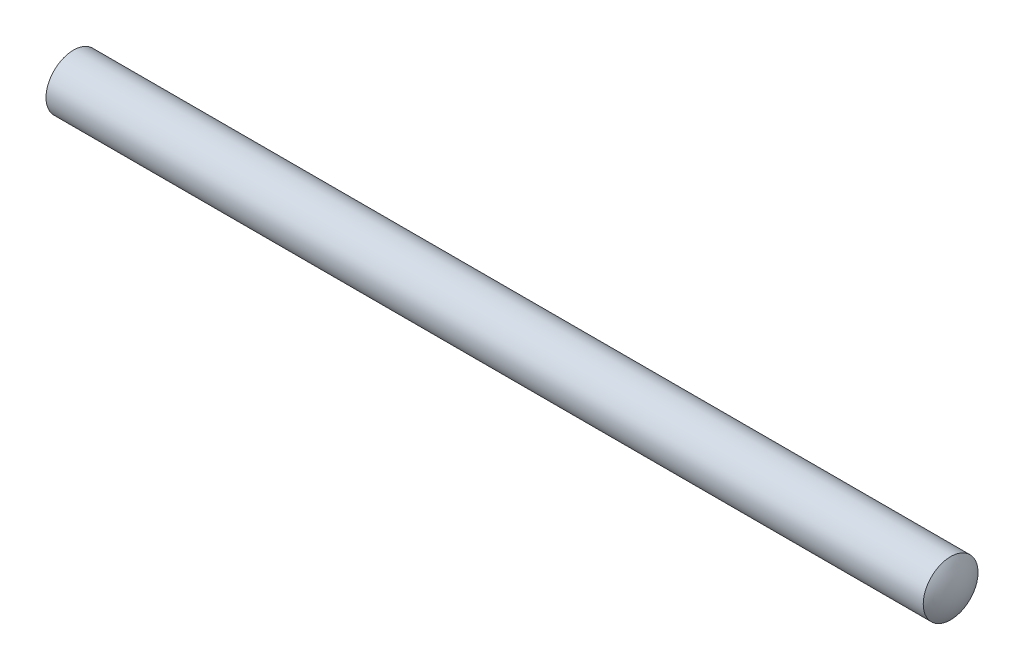
SolidWorks part; units mm, degrees
ref_plane "Front Plane" through (0, 0, 0) normal (0, 0, 1) x (1, 0, 0)
ref_plane "Top Plane" through (0, 0, 0) normal (0, 1, 0) x (1, 0, 0)
ref_plane "Right Plane" through (0, 0, 0) normal (1, 0, 0) x (0, 0, -1)
sketch "Sketch1" plane through (0, 0, 0) normal (1, 0, 0) x (0, 0, -1)
  circle A1 centre (0, 0) radius 2.3812
extrude "Boss-Extrude1" add sketch "Sketch1" along normal up to surface (38.1 mm away) and the other way up to surface (38.1 mm away)
sketch "Sketch2" plane through (0, 0, 0) normal (0, 1, 0) x (1, 0, 0)
  line L1 (38.1, -2.3812) -> (38.1, 2.3812) construction
  line L2 (38.1, -2.3812) -> (38.1, 2.3812)
  line L8 (38.1, -2.3812) -> (38.1, 0)
  line L9 (38.1, -2.3812) -> (38.8938, -2.3812) construction
  line L10 (38.1, 0) -> (38.8938, 0)
  line L11 (38.8938, -2.3812) -> (38.8938, 0) construction
  line L12 (-961.9, 0) -> (49038.1, 0) construction
  arc A0 (38.1, -2.3812) -> (38.8938, 0) centre (34.925, 0) ccw
  dimension "D1" = 0.7937
revolve "Revolve2" add sketch "Sketch2" angle 360 about L10
